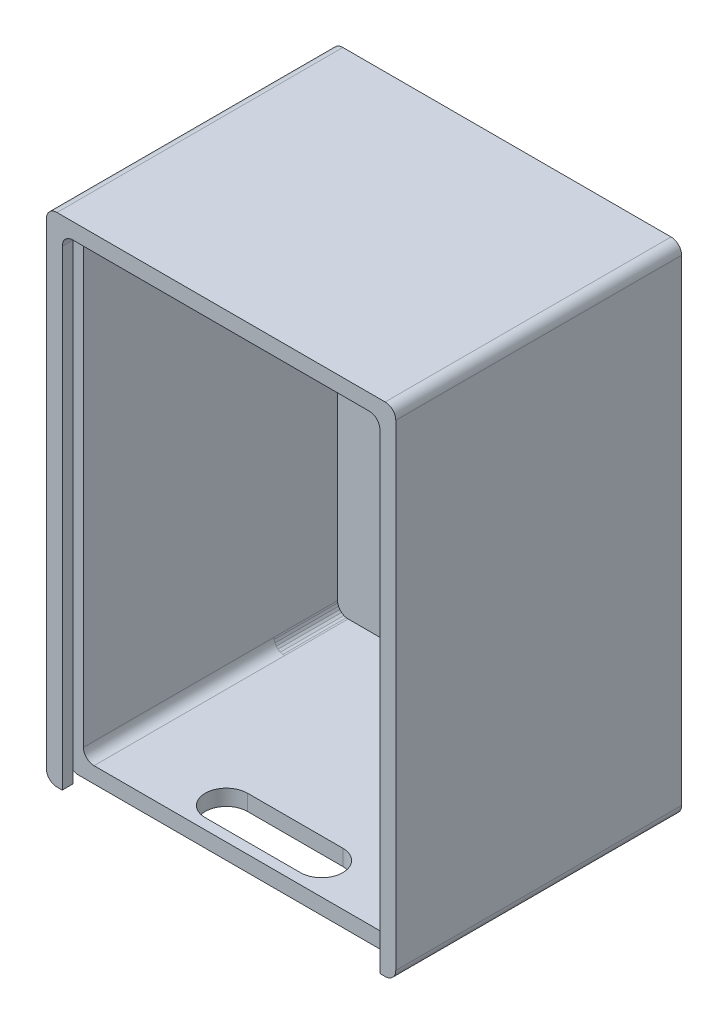
SolidWorks part; units mm, degrees
ref_plane "Plan de face" through (0, 0, 0) normal (0, 0, 1) x (1, 0, 0)
ref_plane "Plan de dessus" through (0, 0, 0) normal (0, 1, 0) x (1, 0, 0)
ref_plane "Plan de droite" through (0, 0, 0) normal (1, 0, 0) x (0, 0, -1)
sketch "Esquisse1" plane through (0, 0, 0) normal (0, 0, 1) x (1, 0, 0)
  line L1 (0, 0) -> (-3.3, 0)
  line L2 (0, 0) -> (0, 4.7)
  line L3 (0, 4.7) -> (-3.3, 4.7)
  line L4 (-3.3, 0) -> (-3.3, 4.7)
  dimension "D1" = 4.7
  dimension "D2" = 3.3
extrude "Boss.-Extru.1" add sketch "Esquisse1" along normal blind 2.7
fillet "Congé4" radius 0.1 1 edges at (-3.3, 4.7, 1.35)
fillet "Congé5" radius 0.1 3 edges at (-3.3, 0, 1.35) (0, 4.7, 1.35) (0, 0, 1.35)
sketch "Esquisse2" plane through (0, 0, 2.7) normal (0, 0, 1) x (1, 0, 0)
  line L0 (0, 0.1) -> (0, 4.6) construction
  line L1 (-3.15, 4.55) -> (-0.15, 4.55)
  line L2 (-3.15, 4.55) -> (-3.15, 0.15)
  line L3 (-3.15, 0.15) -> (-0.15, 0.15)
  line L4 (-0.15, 4.55) -> (-0.15, 0.15)
  line L5 (-3.3, 4.6) -> (-3.3, 0.1) construction
  line L6 (-0.1, 4.7) -> (-3.2, 4.7) construction
  line L7 (-3.2, 0) -> (-0.1, 0) construction
  dimension "D1" = 0.15
  dimension "D2" = 0.15
  dimension "D3" = 0.15
  dimension "D4" = 0.15
extrude "Enlèv. mat.-Extru.2" cut sketch "Esquisse2" against normal blind 2 contours L2 L1 L4 L3
fillet "Congé8" radius 0.1 4 edges at (-3.15, 0.15, 1.7) (-0.15, 0.15, 1.7) (-0.15, 4.55, 1.7) (-3.15, 4.55, 1.7)
sketch "Esquisse3" plane through (0, 0, 0) normal (0, 0, -1) x (-1, 0, 0)
  line L0 (0.1, 4.7) -> (3.2, 4.7) construction
  line L1 (1.2181, 3.9) -> (1.844, 3.9)
  line L2 (1.2181, 3.9) -> (1.2181, 3.2804)
  line L3 (1.2181, 3.2804) -> (1.844, 3.2804)
  line L4 (1.844, 3.9) -> (1.844, 3.2804)
  line L5 (0, 0.1) -> (0, 4.6) construction
  line L6 (3.3, 4.6) -> (3.3, 0.1) construction
  dimension "D1" = 0.8
  dimension "D2" = 1.2181
  dimension "D3" = 1.456
sketch "Esquisse5" plane through (0, 0, 0) normal (0, 0, -1) x (-1, 0, 0)
  line L8 (1.2181, 3.9) -> (1.844, 3.9) construction
  line L9 (1.2, 3.9) -> (2.1, 3.9)
  line L10 (1.2, 3.9) -> (1.2, 3)
  line L11 (1.2, 3) -> (2.1, 3)
  line L12 (2.1, 3.9) -> (2.1, 3)
  line L13 (3.3, 4.6) -> (3.3, 0.1) construction
  line L14 (0, 0.1) -> (0, 4.6) construction
  line L15 (0.1, 4.7) -> (3.2, 4.7) construction
  line L17 (1.2, 3.9) -> (2.2, 3.9)
  line L18 (1.2, 3.9) -> (1.2, 4)
  line L19 (1.2, 4) -> (2.2, 4)
  line L20 (2.2, 3.9) -> (2.2, 4)
  line L21 (2.2, 3.9) -> (2.1, 3.9)
  line L22 (2.2, 3.9) -> (2.2, 2.9)
  line L23 (2.2, 2.9) -> (2.1, 2.9)
  line L24 (2.1, 3.9) -> (2.1, 2.9)
  line L25 (2.1, 2.9) -> (1.1, 2.9)
  line L26 (2.1, 2.9) -> (2.1, 3)
  line L27 (2.1, 3) -> (1.1, 3)
  line L28 (1.1, 2.9) -> (1.1, 3)
  line L29 (1.1, 3) -> (1.2, 3)
  line L30 (1.1, 3) -> (1.1, 4)
  line L31 (1.1, 4) -> (1.2, 4)
  line L32 (1.2, 3) -> (1.2, 4)
  dimension "D1" = 1.2
  dimension "D2" = 1.2
  dimension "D3" = 0.8
  dimension "D4" = 0.9
  dimension "D5" = 0.9
  dimension "D6" = 0.1
  dimension "D7" = 0.1
  dimension "D8" = 0.1
  dimension "D9" = 0.1
extrude "Boss.-Extru.3" add sketch "Esquisse5" along normal blind 0.5 contours L18 L17 L20 L19 | L30 L29 L32 L31 | L26 L25 L28 L27 | L22 L21 L24 L23
sketch "Esquisse6" plane through (0, 0, 0) normal (0, 0, -1) x (-1, 0, 0)
  line L1 (1.2, 3.9) -> (2.1, 3.9)
  line L2 (1.2, 3.9) -> (1.2, 3)
  line L3 (1.2, 3) -> (2.1, 3)
  line L4 (2.1, 3.9) -> (2.1, 3)
extrude "Enlèv. mat.-Extru.4" cut sketch "Esquisse6" against normal blind 0.5
sketch "Esquisse7" plane through (0, 0, 2.7) normal (0, 0, 1) x (1, 0, 0)
  line L0 (-3.15, 0.25) -> (-3.15, 0)
  line L1 (-3.2, 0) -> (-0.1, 0) construction
  line L2 (-0.15, 0.25) -> (-0.15, 0)
  line L3 (-0.15, 0) -> (-3.15, 0)
  line L4 (-3.15, 0.25) -> (-3.1464, 0.2234)
  line L5 (-3.1464, 0.2234) -> (-3.1362, 0.1993)
  line L6 (-3.1362, 0.1993) -> (-3.1207, 0.1793)
  line L7 (-3.1207, 0.1793) -> (-3.1018, 0.1645)
  line L8 (-3.1018, 0.1645) -> (-3.0759, 0.1534)
  line L9 (-3.0759, 0.1534) -> (-3.05, 0.15)
  line L10 (-3.05, 0.15) -> (-0.25, 0.15)
  line L11 (-0.25, 0.15) -> (-0.2234, 0.1536)
  line L12 (-0.2234, 0.1536) -> (-0.1993, 0.1638)
  line L13 (-0.1993, 0.1638) -> (-0.1793, 0.1793)
  line L14 (-0.1793, 0.1793) -> (-0.1638, 0.1993)
  line L15 (-0.1638, 0.1993) -> (-0.1536, 0.2234)
  line L16 (-0.1536, 0.2234) -> (-0.15, 0.25)
  arc A0 (-3.15, 0.25) -> (-3.05, 0.15) centre (-3.05, 0.25) ccw construction
  arc A1 (-3.15, 0.25) -> (-3.05, 0.15) centre (-3.05, 0.25) ccw construction
  arc A2 (-0.25, 0.15) -> (-0.15, 0.25) centre (-0.25, 0.25) ccw construction
  arc A3 (-0.25, 0.15) -> (-0.15, 0.25) centre (-0.25, 0.25) ccw construction
extrude "Enlèv. mat.-Extru.5" cut sketch "Esquisse7" against normal blind 0.2
sketch "Esquisse8" plane through (-3.15, 0, 0) normal (1, 0, 0) x (0, 0, -1)
  line L0 (-2.7, 4.45) -> (-2.7, 0) construction
  line L1 (-2.5, 0) -> (-2.7, 0)
  line L2 (-2.5, 0) -> (-2.5, 4.45)
  line L3 (-2.5, 4.45) -> (-2.7, 4.45)
  line L6 (-2.6, 0) -> (-2.6, 4.4523)
  line L9 (-2.6, 0) -> (-2.5, 0)
  line L10 (-2.6, 0) -> (-2.6, 4.45)
  line L11 (-2.6, 4.45) -> (-2.5, 4.45)
  line L12 (-2.5, 0) -> (-2.5, 4.45)
  dimension "D1" = 0.1
extrude "Enlèv. mat.-Extru.6" cut sketch "Esquisse8" against normal blind 0.1 contours L10 L9 L12 L11
sketch "Esquisse9" plane through (-0.15, 0, 0) normal (-1, 0, 0) x (0, 0, 1)
  line L0 (2.5, 0) -> (2.7, 0)
  line L2 (2.6, 0) -> (2.6, 4.45)
  line L3 (2.7, 4.45) -> (0.7, 4.45) construction
  line L4 (2.6, 4.45) -> (2.5, 4.45)
  line L6 (2.5, 0) -> (2.5, 4.45)
sketch "Esquisse10" plane through (-0.15, 0, 0) normal (-1, 0, 0) x (0, 0, 1)
  line L1 (2.5, 4.45) -> (2.6, 4.45)
  line L2 (2.5, 4.45) -> (2.5, 0)
  line L3 (2.5, 0) -> (2.6, 0)
  line L4 (2.6, 4.45) -> (2.6, 0)
extrude "Enlèv. mat.-Extru.7" cut sketch "Esquisse10" against normal blind 0.1
sketch "Esquisse11" plane through (0, 0, 0.5) normal (0, 0, -1) x (-1, 0, 0)
  line L1 (1.2, 3.9) -> (2.1, 3.9)
  line L2 (1.2, 3.9) -> (1.2, 3)
  line L3 (1.2, 3) -> (2.1, 3)
  line L4 (2.1, 3.9) -> (2.1, 3)
extrude "Enlèv. mat.-Extru.8" cut sketch "Esquisse11" against normal blind 1
sketch "Esquisse12" plane through (0, 0, 0) normal (0, -1, 0) x (-1, 0, 0)
  line L0 (3.2, -2.5) -> (0.1, -2.5) construction
  line L1 (2.1, -2.4) -> (1.2, -2.4)
  line L2 (2.1, -2.4) -> (2.1, -2)
  line L3 (2.1, -2) -> (1.2, -2)
  line L4 (1.2, -2.4) -> (1.2, -2)
  line L5 (0.1, 0) -> (0.1, -2.5) construction
  circle A0 centre (2.1, -2.2) radius 0.2
  circle A1 centre (1.2, -2.2) radius 0.2
  dimension "D1" = 0.4
  dimension "D2" = 0.1
  dimension "D3" = 0.9
  dimension "D4" = 1.1
extrude "Enlèv. mat.-Extru.9" cut sketch "Esquisse12" against normal blind 1.1 contours L2 L1 L4 L3 | A0 | A1
sketch "Esquisse15" plane through (0, 0, 0.7) normal (0, 0, 1) x (1, 0, 0)
  line L0 (-3.05, 4.55) -> (-3.0746, 4.5469)
  line L1 (-3.0746, 4.5469) -> (-3.099, 4.5372)
  line L2 (-3.099, 4.5372) -> (-3.1207, 4.5207)
  line L3 (-3.1207, 4.5207) -> (-3.1356, 4.5017)
  line L4 (-3.1356, 4.5017) -> (-3.1461, 4.4777)
  line L5 (-3.1461, 4.4777) -> (-3.15, 4.45)
  line L6 (-3.15, 4.45) -> (-3.15, 0.25)
  line L7 (-3.15, 0.25) -> (-3.1484, 0.2323)
  line L8 (-3.1484, 0.2323) -> (-3.1408, 0.2082)
  line L9 (-3.1408, 0.2082) -> (-3.1282, 0.1876)
  line L10 (-3.1282, 0.1876) -> (-3.112, 0.1715)
  line L11 (-3.112, 0.1715) -> (-3.0897, 0.1582)
  line L12 (-3.0897, 0.1582) -> (-3.0666, 0.1514)
  line L13 (-3.0666, 0.1514) -> (-3.05, 0.15)
  line L14 (-3.05, 0.15) -> (-0.25, 0.15)
  line L15 (-3.05, 0.15) -> (-0.25, 0.15) construction
  line L16 (-0.25, 0.15) -> (-0.2323, 0.1516)
  line L17 (-0.2323, 0.1516) -> (-0.2103, 0.1582)
  line L18 (-0.2103, 0.1582) -> (-0.188, 0.1715)
  line L19 (-0.188, 0.1715) -> (-0.1712, 0.1884)
  line L20 (-0.1712, 0.1884) -> (-0.1584, 0.2098)
  line L21 (-0.1584, 0.2098) -> (-0.1513, 0.2339)
  line L22 (-0.1513, 0.2339) -> (-0.15, 0.25)
  line L23 (-0.15, 0.25) -> (-0.15, 4.45)
  line L24 (-0.15, 4.45) -> (-0.1539, 4.4777)
  line L25 (-0.1539, 4.4777) -> (-0.1644, 4.5017)
  line L26 (-0.1644, 4.5017) -> (-0.1793, 4.5207)
  line L27 (-0.1793, 4.5207) -> (-0.1983, 4.5356)
  line L28 (-0.1983, 4.5356) -> (-0.2223, 4.5461)
  line L29 (-0.2223, 4.5461) -> (-0.25, 4.55)
  line L30 (-0.25, 4.55) -> (-3.05, 4.55)
  arc A0 (-3.05, 4.55) -> (-3.15, 4.45) centre (-3.05, 4.45) ccw construction
  arc A1 (-3.15, 0.25) -> (-3.05, 0.15) centre (-3.05, 0.25) ccw construction
  arc A2 (-0.25, 0.15) -> (-0.15, 0.25) centre (-0.25, 0.25) ccw construction
  arc A3 (-0.15, 4.45) -> (-0.25, 4.55) centre (-0.25, 4.45) ccw construction
extrude "Enlèv. mat.-Extru.11" cut sketch "Esquisse15" against normal blind 0.6
